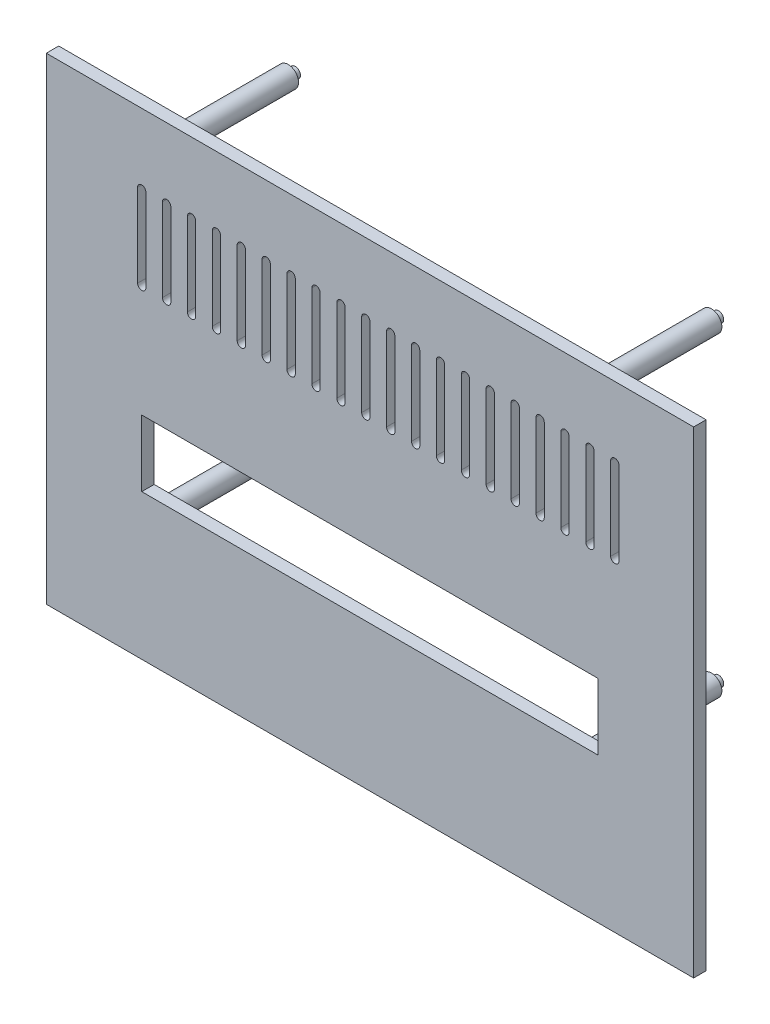
SolidWorks part; units mm, degrees
material "ABS"
ref_plane "前视基准面" through (0, 0, 0) normal (0, 0, 1) x (1, 0, 0)
ref_plane "上视基准面" through (0, 0, 0) normal (0, 1, 0) x (1, 0, 0)
ref_plane "右视基准面" through (0, 0, 0) normal (1, 0, 0) x (0, 0, -1)
sketch "草图1" plane through (0, 0, -2003.6217) normal (0, 0, 1) x (1, 0, 0)
  line L1 (73.6288, 67.7768) -> (217.6288, 67.7768)
  line L2 (73.6288, 67.7768) -> (73.6288, -36.2232)
  line L3 (73.6288, -36.2232) -> (217.6288, -36.2232)
  line L4 (217.6288, 67.7768) -> (217.6288, -36.2232)
  line L5 (220.6288, -39.2232) -> (70.6288, -39.2232)
  line L6 (220.6288, -39.2232) -> (220.6288, 70.7768)
  line L7 (220.6288, 70.7768) -> (70.6288, 70.7768)
  line L8 (70.6288, -39.2232) -> (70.6288, 70.7768)
sketch "草图2" plane through (0, 0, -2003.6217) normal (0, 0, 1) x (1, 0, 0)
  line L0 (90.6288, 35.7768) -> (90.6288, 55.7768) construction
  line L1 (67.6288, 72.7768) -> (223.6288, 72.7768)
  line L2 (67.6288, 72.7768) -> (67.6288, -42.2232)
  line L3 (67.6288, -42.2232) -> (223.6288, -42.2232)
  line L4 (223.6288, 72.7768) -> (223.6288, -42.2232)
  line L5 (90.6288, 8.7768) -> (200.6288, 8.7768)
  line L6 (90.6288, 8.7768) -> (90.6288, -7.2232)
  line L7 (90.6288, -7.2232) -> (200.6288, -7.2232)
  line L8 (200.6288, 8.7768) -> (200.6288, -7.2232)
  line L9 (89.6288, 35.7768) -> (89.6288, 55.7768)
  line L10 (91.6288, 35.7768) -> (91.6288, 55.7768)
  line L11 (96.6288, 35.7768) -> (96.6288, 55.7768) construction
  line L12 (95.6288, 35.7768) -> (95.6288, 55.7768)
  line L13 (97.6288, 35.7768) -> (97.6288, 55.7768)
  line L14 (102.6288, 35.7768) -> (102.6288, 55.7768) construction
  line L15 (101.6288, 35.7768) -> (101.6288, 55.7768)
  line L16 (103.6288, 35.7768) -> (103.6288, 55.7768)
  line L17 (108.6288, 35.7768) -> (108.6288, 55.7768) construction
  line L18 (107.6288, 35.7768) -> (107.6288, 55.7768)
  line L19 (109.6288, 35.7768) -> (109.6288, 55.7768)
  line L20 (114.6288, 35.7768) -> (114.6288, 55.7768) construction
  line L21 (113.6288, 35.7768) -> (113.6288, 55.7768)
  line L22 (115.6288, 35.7768) -> (115.6288, 55.7768)
  line L23 (120.6288, 35.7768) -> (120.6288, 55.7768) construction
  line L24 (119.6288, 35.7768) -> (119.6288, 55.7768)
  line L25 (121.6288, 35.7768) -> (121.6288, 55.7768)
  line L26 (126.6288, 35.7768) -> (126.6288, 55.7768) construction
  line L27 (125.6288, 35.7768) -> (125.6288, 55.7768)
  line L28 (127.6288, 35.7768) -> (127.6288, 55.7768)
  line L29 (132.6288, 35.7768) -> (132.6288, 55.7768) construction
  line L30 (131.6288, 35.7768) -> (131.6288, 55.7768)
  line L31 (133.6288, 35.7768) -> (133.6288, 55.7768)
  line L32 (138.6288, 35.7768) -> (138.6288, 55.7768) construction
  line L33 (137.6288, 35.7768) -> (137.6288, 55.7768)
  line L34 (139.6288, 35.7768) -> (139.6288, 55.7768)
  line L35 (144.6288, 35.7768) -> (144.6288, 55.7768) construction
  line L36 (143.6288, 35.7768) -> (143.6288, 55.7768)
  line L37 (145.6288, 35.7768) -> (145.6288, 55.7768)
  line L38 (150.6288, 35.7768) -> (150.6288, 55.7768) construction
  line L39 (149.6288, 35.7768) -> (149.6288, 55.7768)
  line L40 (151.6288, 35.7768) -> (151.6288, 55.7768)
  line L41 (156.6288, 35.7768) -> (156.6288, 55.7768) construction
  line L42 (155.6288, 35.7768) -> (155.6288, 55.7768)
  line L43 (157.6288, 35.7768) -> (157.6288, 55.7768)
  line L44 (162.6288, 35.7768) -> (162.6288, 55.7768) construction
  line L45 (161.6288, 35.7768) -> (161.6288, 55.7768)
  line L46 (163.6288, 35.7768) -> (163.6288, 55.7768)
  line L47 (168.6288, 35.7768) -> (168.6288, 55.7768) construction
  line L48 (167.6288, 35.7768) -> (167.6288, 55.7768)
  line L49 (169.6288, 35.7768) -> (169.6288, 55.7768)
  line L50 (174.6288, 35.7768) -> (174.6288, 55.7768) construction
  line L51 (173.6288, 35.7768) -> (173.6288, 55.7768)
  line L52 (175.6288, 35.7768) -> (175.6288, 55.7768)
  line L53 (180.6288, 35.7768) -> (180.6288, 55.7768) construction
  line L54 (179.6288, 35.7768) -> (179.6288, 55.7768)
  line L55 (181.6288, 35.7768) -> (181.6288, 55.7768)
  line L56 (186.6288, 35.7768) -> (186.6288, 55.7768) construction
  line L57 (185.6288, 35.7768) -> (185.6288, 55.7768)
  line L58 (187.6288, 35.7768) -> (187.6288, 55.7768)
  line L59 (192.6288, 35.7768) -> (192.6288, 55.7768) construction
  line L60 (191.6288, 35.7768) -> (191.6288, 55.7768)
  line L61 (193.6288, 35.7768) -> (193.6288, 55.7768)
  line L62 (198.6288, 35.7768) -> (198.6288, 55.7768) construction
  line L63 (197.6288, 35.7768) -> (197.6288, 55.7768)
  line L64 (199.6288, 35.7768) -> (199.6288, 55.7768)
  line L65 (204.6288, 35.7768) -> (204.6288, 55.7768) construction
  line L66 (203.6288, 35.7768) -> (203.6288, 55.7768)
  line L67 (205.6288, 35.7768) -> (205.6288, 55.7768)
  line L70 (153, -3) -> (153, 112) construction
  arc A0 (89.6288, 35.7768) -> (91.6288, 35.7768) centre (90.6288, 35.7768) ccw
  arc A1 (91.6288, 55.7768) -> (89.6288, 55.7768) centre (90.6288, 55.7768) ccw
  arc A2 (95.6288, 35.7768) -> (97.6288, 35.7768) centre (96.6288, 35.7768) ccw
  arc A3 (97.6288, 55.7768) -> (95.6288, 55.7768) centre (96.6288, 55.7768) ccw
  arc A4 (101.6288, 35.7768) -> (103.6288, 35.7768) centre (102.6288, 35.7768) ccw
  arc A5 (103.6288, 55.7768) -> (101.6288, 55.7768) centre (102.6288, 55.7768) ccw
  arc A6 (107.6288, 35.7768) -> (109.6288, 35.7768) centre (108.6288, 35.7768) ccw
  arc A7 (109.6288, 55.7768) -> (107.6288, 55.7768) centre (108.6288, 55.7768) ccw
  arc A8 (113.6288, 35.7768) -> (115.6288, 35.7768) centre (114.6288, 35.7768) ccw
  arc A9 (115.6288, 55.7768) -> (113.6288, 55.7768) centre (114.6288, 55.7768) ccw
  arc A10 (119.6288, 35.7768) -> (121.6288, 35.7768) centre (120.6288, 35.7768) ccw
  arc A11 (121.6288, 55.7768) -> (119.6288, 55.7768) centre (120.6288, 55.7768) ccw
  arc A12 (125.6288, 35.7768) -> (127.6288, 35.7768) centre (126.6288, 35.7768) ccw
  arc A13 (127.6288, 55.7768) -> (125.6288, 55.7768) centre (126.6288, 55.7768) ccw
  arc A14 (131.6288, 35.7768) -> (133.6288, 35.7768) centre (132.6288, 35.7768) ccw
  arc A15 (133.6288, 55.7768) -> (131.6288, 55.7768) centre (132.6288, 55.7768) ccw
  arc A16 (137.6288, 35.7768) -> (139.6288, 35.7768) centre (138.6288, 35.7768) ccw
  arc A17 (139.6288, 55.7768) -> (137.6288, 55.7768) centre (138.6288, 55.7768) ccw
  arc A18 (143.6288, 35.7768) -> (145.6288, 35.7768) centre (144.6288, 35.7768) ccw
  arc A19 (145.6288, 55.7768) -> (143.6288, 55.7768) centre (144.6288, 55.7768) ccw
  arc A20 (149.6288, 35.7768) -> (151.6288, 35.7768) centre (150.6288, 35.7768) ccw
  arc A21 (151.6288, 55.7768) -> (149.6288, 55.7768) centre (150.6288, 55.7768) ccw
  arc A22 (155.6288, 35.7768) -> (157.6288, 35.7768) centre (156.6288, 35.7768) ccw
  arc A23 (157.6288, 55.7768) -> (155.6288, 55.7768) centre (156.6288, 55.7768) ccw
  arc A24 (161.6288, 35.7768) -> (163.6288, 35.7768) centre (162.6288, 35.7768) ccw
  arc A25 (163.6288, 55.7768) -> (161.6288, 55.7768) centre (162.6288, 55.7768) ccw
  arc A26 (167.6288, 35.7768) -> (169.6288, 35.7768) centre (168.6288, 35.7768) ccw
  arc A27 (169.6288, 55.7768) -> (167.6288, 55.7768) centre (168.6288, 55.7768) ccw
  arc A28 (173.6288, 35.7768) -> (175.6288, 35.7768) centre (174.6288, 35.7768) ccw
  arc A29 (175.6288, 55.7768) -> (173.6288, 55.7768) centre (174.6288, 55.7768) ccw
  arc A30 (179.6288, 35.7768) -> (181.6288, 35.7768) centre (180.6288, 35.7768) ccw
  arc A31 (181.6288, 55.7768) -> (179.6288, 55.7768) centre (180.6288, 55.7768) ccw
  arc A32 (185.6288, 35.7768) -> (187.6288, 35.7768) centre (186.6288, 35.7768) ccw
  arc A33 (187.6288, 55.7768) -> (185.6288, 55.7768) centre (186.6288, 55.7768) ccw
  arc A34 (191.6288, 35.7768) -> (193.6288, 35.7768) centre (192.6288, 35.7768) ccw
  arc A35 (193.6288, 55.7768) -> (191.6288, 55.7768) centre (192.6288, 55.7768) ccw
  arc A36 (197.6288, 35.7768) -> (199.6288, 35.7768) centre (198.6288, 35.7768) ccw
  arc A37 (199.6288, 55.7768) -> (197.6288, 55.7768) centre (198.6288, 55.7768) ccw
  arc A38 (203.6288, 35.7768) -> (205.6288, 35.7768) centre (204.6288, 35.7768) ccw
  arc A39 (205.6288, 55.7768) -> (203.6288, 55.7768) centre (204.6288, 55.7768) ccw
  point P16 (90.6288, 45.7768)
  point P25 (96.6288, 45.7768)
  point P32 (102.6288, 45.7768)
  point P39 (108.6288, 45.7768)
  point P46 (114.6288, 45.7768)
  point P53 (120.6288, 45.7768)
  point P60 (126.6288, 45.7768)
  point P67 (132.6288, 45.7768)
  point P74 (138.6288, 45.7768)
  point P81 (144.6288, 45.7768)
  point P88 (150.6288, 45.7768)
  point P95 (156.6288, 45.7768)
  point P102 (162.6288, 45.7768)
  point P109 (168.6288, 45.7768)
  point P116 (174.6288, 45.7768)
  point P123 (180.6288, 45.7768)
  point P130 (186.6288, 45.7768)
  point P137 (192.6288, 45.7768)
  point P144 (198.6288, 45.7768)
  point P151 (204.6288, 45.7768)
  dimension "D1" = 1
  dimension "D3" = 3.6288
  dimension "D2" = 20
extrude "凸台-拉伸1" add sketch "草图2" along normal blind 3
extrude "凸台-拉伸2" add sketch "草图1" against normal blind 2
sketch "草图3" plane through (0, 0, -2003.6217) normal (0, 0, -1) x (-1, 0, 0)
  circle A0 centre (-196.6288, 65.7768) radius 2.5
  circle A1 centre (-94.6288, 65.7768) radius 2.5
  circle A2 centre (-94.6288, -10.2232) radius 2.5
  circle A3 centre (-196.6288, -10.2232) radius 2.5
  dimension "D1" = 5
extrude "凸台-拉伸3" add sketch "草图3" along normal blind 28.3
sketch "草图5" plane through (0, 0, -2031.9217) normal (0, 0, -1) x (-1, 0, 0)
  circle A0 centre (-196.6288, 65.7768) radius 1.25
  circle A1 centre (-94.6288, 65.7768) radius 1.25
  circle A2 centre (-94.6288, -10.2232) radius 1.25
  circle A3 centre (-196.6288, -10.2232) radius 1.25
  dimension "D1" = 2.5
extrude "凸台-拉伸4" add sketch "草图5" along normal blind 1.7
